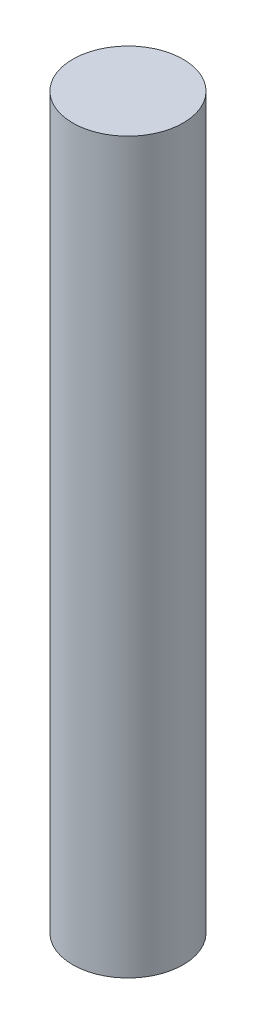
SolidWorks part; units mm, degrees
material "1.2210 (115CrV3)"
ref_plane "Front Plane" through (0, 0, 0) normal (0, 0, 1) x (1, 0, 0)
ref_plane "Top Plane" through (0, 0, 0) normal (0, 1, 0) x (1, 0, 0)
ref_plane "Right Plane" through (0, 0, 0) normal (1, 0, 0) x (0, 0, -1)
sketch "Sketch1" plane through (0, 0, 0) normal (0, 1, 0) x (1, 0, 0)
  circle A0 centre (0, 0) radius 25
  dimension "D1" = 50
extrude "Boss-Extrude1" add sketch "Sketch1" along normal blind 330
